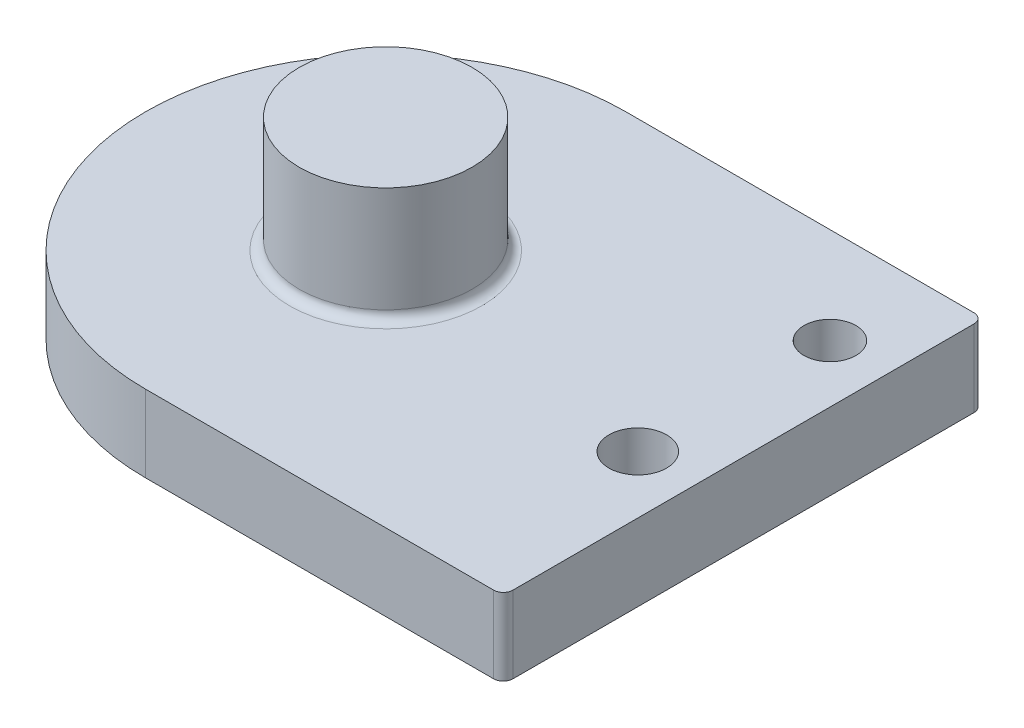
SolidWorks part; units mm, degrees
material "聚脂树脂"
ref_plane "前视基准面" through (0, 0, 0) normal (0, 0, 1) x (1, 0, 0)
ref_plane "上视基准面" through (0, 0, 0) normal (0, 1, 0) x (1, 0, 0)
ref_plane "右视基准面" through (0, 0, 0) normal (1, 0, 0) x (0, 0, -1)
sketch "草图1" plane through (0, 0, 0) normal (0, 1, 0) x (1, 0, 0)
  line L1 (5, 0) -> (14.3103, 0)
  line L3 (5, 12.5) -> (14.3103, 12.5)
  line L4 (14.3103, 0) -> (14.3103, 12.5)
  arc A0 (5, 12.5) -> (5, 0) centre (5, 6.25) ccw
  dimension "D1" = 12.5
extrude "凸台-拉伸1" add sketch "草图1" along normal blind 2
sketch "草图2" plane through (0, 2, 0) normal (0, 1, 0) x (1, 0, 0)
  circle A0 centre (5, 6.25) radius 2.25
  dimension "D1" = 4.5
extrude "凸台-拉伸2" add sketch "草图2" along normal blind 3
sketch "草图3" plane through (0, 2, 0) normal (0, 1, 0) x (1, 0, 0)
  line L0 (14.3103, 0) -> (14.3103, 12.5) construction
  line L1 (14.3103, 12.5) -> (5, 12.5) construction
  circle A0 centre (12.8103, 10) radius 0.6766
  circle A1 centre (12.8103, 5) radius 0.7507
  dimension "D1" = 5
  dimension "D2" = 1.5
  dimension "D3" = 2.5
extrude "切除-拉伸1" cut sketch "草图3" against normal blind 10
fillet "圆角1" radius 0.25 1 edges at (5, 2, -4)
fillet "圆角2" radius 0.25 2 edges at (14.3103, 1, 0) (14.3103, 1, -12.5)
